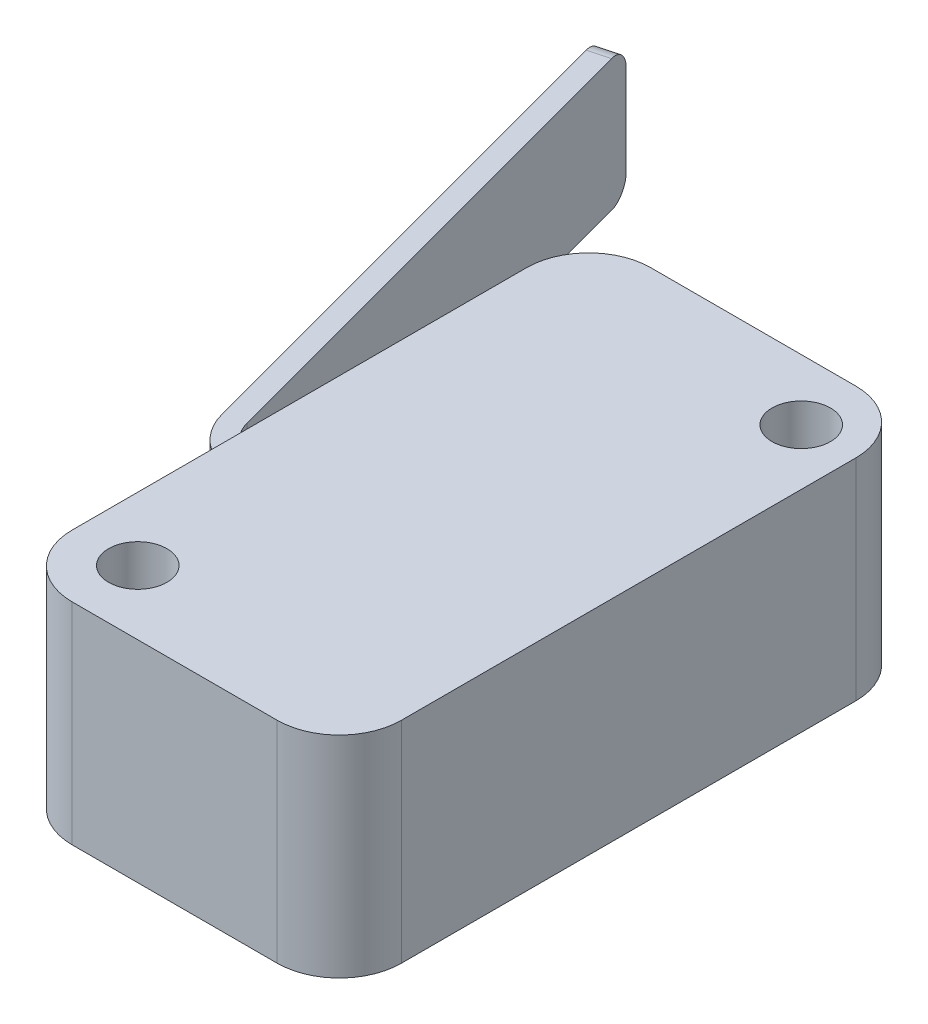
SolidWorks part; units mm, degrees
ref_plane "Front Plane" through (0, 0, 0) normal (0, 0, 1) x (1, 0, 0)
ref_plane "Top Plane" through (0, 0, 0) normal (0, 1, 0) x (1, 0, 0)
ref_plane "Right Plane" through (0, 0, 0) normal (1, 0, 0) x (0, 0, -1)
sketch "Sketch1" plane through (0, 0, 0) normal (0, 1, 0) x (1, 0, 0)
  line L1 (-7.9502, -13.97) -> (7.9502, -13.97)
  line L2 (-7.9502, -13.97) -> (-7.9502, 13.97)
  line L3 (-7.9502, 13.97) -> (7.9502, 13.97)
  line L4 (7.9502, -13.97) -> (7.9502, 13.97)
  line L5 (-7.9502, -13.97) -> (7.9502, 13.97) construction
  line L6 (-7.9502, 13.97) -> (7.9502, -13.97) construction
  point P0 (0, 0)
  dimension "D1" = 27.94
  dimension "D2" = 15.9004
extrude "Boss-Extrude1" add sketch "Sketch1" along normal mid plane 10.16
fillet "Fillet1" radius 3 4 edges at (7.9502, 0, -13.97) (-7.9502, 0, -13.97) (7.9502, 0, 13.97) (-7.9502, 0, 13.97)
sketch "Sketch2" plane through (0, 0, 0) normal (0, 1, 0) x (1, 0, 0)
  line L0 (-7.9502, 10.97) -> (-7.9502, -10.97) construction
  line L1 (7.9502, -10.97) -> (7.9502, -13.97) construction
  line L2 (7.9502, -13.97) -> (4.9502, -13.97) construction
  line L3 (4.9502, 13.97) -> (-4.9502, 13.97) construction
  line L6 (-17.7732, 24.3792) -> (-11.0744, -0.6208)
  line L7 (-8.1767, -2.8444) -> (-3.7494, -2.8444)
  line L8 (-16.8072, 24.638) -> (-10.1085, -0.362)
  line L9 (-8.1767, -1.8444) -> (-3.7494, -1.8444)
  line L10 (-17.7732, 24.3792) -> (-16.8072, 24.638)
  line L11 (-3.7494, -1.8444) -> (-3.7494, -2.8444)
  arc A0 (4.9502, -13.97) -> (7.9502, -10.97) centre (4.9502, -10.97) ccw construction
  arc A1 (-11.0744, -0.6208) -> (-8.1767, -2.8444) centre (-8.1767, 0.1556) ccw
  arc A2 (-10.1085, -0.362) -> (-8.1767, -1.8444) centre (-8.1767, 0.1556) ccw
  dimension "D3" = 3
  dimension "D1" = 15
  dimension "D2" = 25
  dimension "D5" = 10.668
  dimension "D4" = 1
extrude "Boss-Extrude2" add sketch "Sketch2" against normal mid plane 6.35
fillet "Fillet2" radius 1 2 edges at (-17.2902, -3.175, -24.5086) (-17.2902, 3.175, -24.5086)
sketch "Sketch3" plane through (0, 5.08, 0) normal (0, 1, 0) x (1, 0, 0)
  line L0 (5.2482, 11.0333) -> (-4.8844, -10.8661) construction
  circle A0 centre (5.2482, 11.0333) radius 1.4097
  circle A1 centre (-4.8844, -10.8661) radius 1.4097
  dimension "D1" = 2.8194
  dimension "D2" = 24.13
extrude "Cut-Extrude1" cut sketch "Sketch3" against normal blind 16.35
